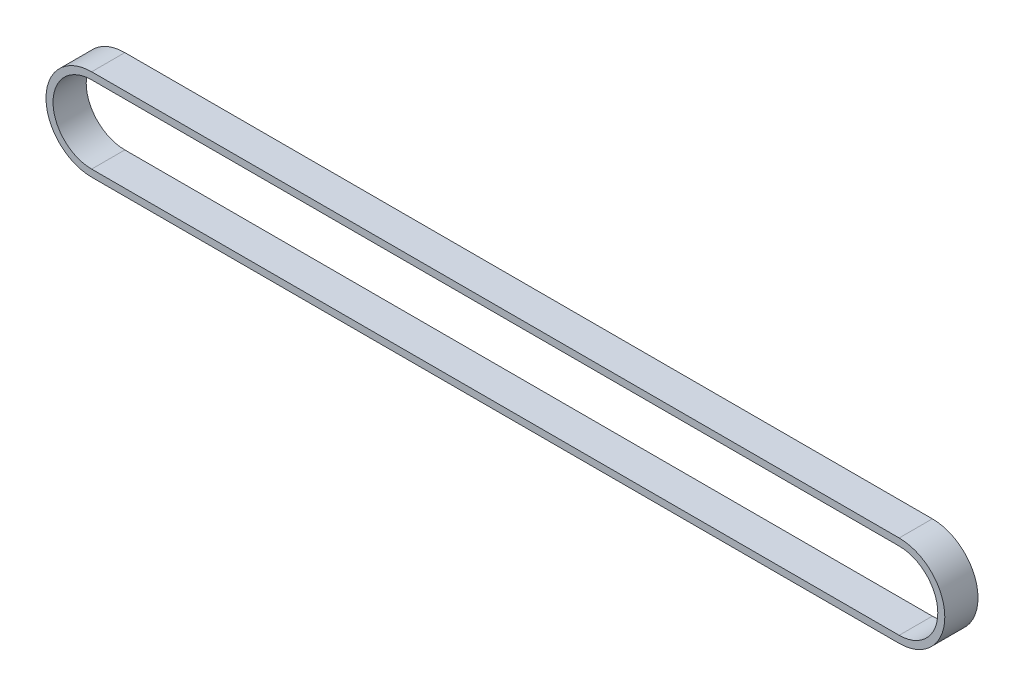
SolidWorks part; units mm, degrees
material "Rubber"
ref_plane "Front Plane" through (0, 0, 0) normal (0, 0, 1) x (1, 0, 0)
ref_plane "Top Plane" through (0, 0, 0) normal (0, 1, 0) x (1, 0, 0)
ref_plane "Right Plane" through (0, 0, 0) normal (1, 0, 0) x (0, 0, -1)
sketch "Sketch1" plane through (0, 0, 0) normal (0, 0, 1) x (1, 0, 0)
  line L0 (0, 20.6375) -> (364.998, 20.6375)
  line L1 (0, 17.4625) -> (364.998, 17.4625)
  line L2 (0, -17.4625) -> (364.998, -17.4625)
  line L3 (0, -20.6375) -> (364.998, -20.6375)
  arc A0 (0, 17.4625) -> (0, -17.4625) centre (0, 0) ccw
  arc A1 (0, 20.6375) -> (0, -20.6375) centre (0, 0) ccw
  arc A2 (364.998, -20.6375) -> (364.998, 20.6375) centre (364.998, 0) ccw
  arc A3 (364.998, -17.4625) -> (364.998, 17.4625) centre (364.998, 0) ccw
  dimension "D1" = 20.6375
  dimension "D2" = 17.4625
  dimension "D3" = 364.998
extrude "Boss-Extrude1" add sketch "Sketch1" along normal blind 15
